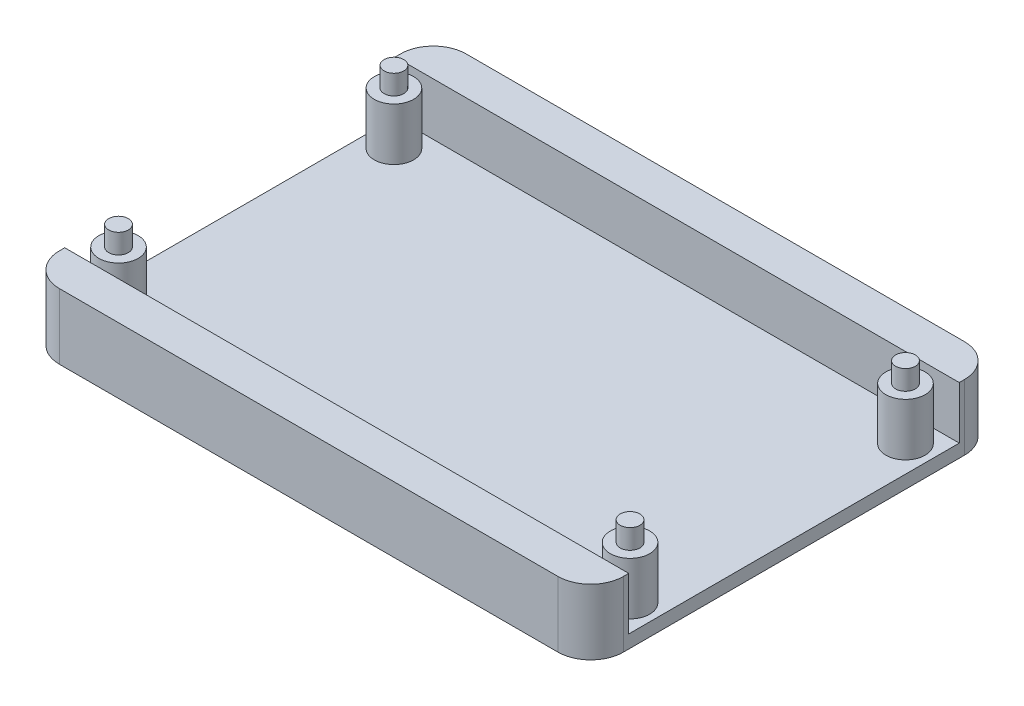
SolidWorks part; units mm, degrees
ref_plane "前视基准面" through (0, 0, 0) normal (0, 0, 1) x (1, 0, 0)
ref_plane "上视基准面" through (0, 0, 0) normal (0, 1, 0) x (1, 0, 0)
ref_plane "右视基准面" through (0, 0, 0) normal (1, 0, 0) x (0, 0, -1)
other "Configuration Table"
sketch "草图1" plane through (0, 0, 0) normal (0, 1, 0) x (1, 0, 0)
  line L1 (43, -31) -> (-43, -31)
  line L2 (43, -31) -> (43, 31)
  line L3 (43, 31) -> (-43, 31)
  line L4 (-43, -31) -> (-43, 31)
  line L5 (43, -31) -> (-43, 31) construction
  line L6 (43, 31) -> (-43, -31) construction
  point P0 (0, 0)
  dimension "D1" = 86
  dimension "D2" = 62
extrude "凸台-拉伸1" add sketch "草图1" along normal blind 10
sketch "草图2" plane through (0, 10, 0) normal (0, 1, 0) x (1, 0, 0)
  line L0 (-43, 31) -> (-43, -31) construction
  line L1 (43, -25.2) -> (-43, -25.2)
  line L2 (43, -25.2) -> (43, 25.2)
  line L3 (43, 25.2) -> (-43, 25.2)
  line L4 (-43, -25.2) -> (-43, 25.2)
  line L5 (43, -25.2) -> (-43, 25.2) construction
  line L6 (43, 25.2) -> (-43, -25.2) construction
  circle A0 centre (-39, 21) radius 3
  circle A1 centre (39, 21) radius 3
  circle A2 centre (39, -21) radius 3
  circle A3 centre (-39, -21) radius 3
  point P0 (0, 0)
  dimension "D2" = 21
  dimension "D6" = 6
  dimension "D1" = 50.4
  dimension "D3" = 39
  dimension "D4" = 2
  dimension "D5" = 2
extrude "切除-拉伸1" cut sketch "草图2" against normal blind 8
sketch "草图3" plane through (0, 10, 0) normal (0, 1, 0) x (1, 0, 0)
  circle A0 centre (-39, 21) radius 1.5
  circle A1 centre (39, 21) radius 1.5
  circle A2 centre (39, -21) radius 1.5
  circle A3 centre (-39, -21) radius 1.5
  dimension "D1" = 3
  dimension "D2" = 2
  dimension "D3" = 2
extrude "凸台-拉伸2" add sketch "草图3" along normal blind 3
fillet "圆角1" radius 5 4 edges at (43, 5, -31) (43, 5, 31) (-43, 5, 31) (-43, 5, -31)
